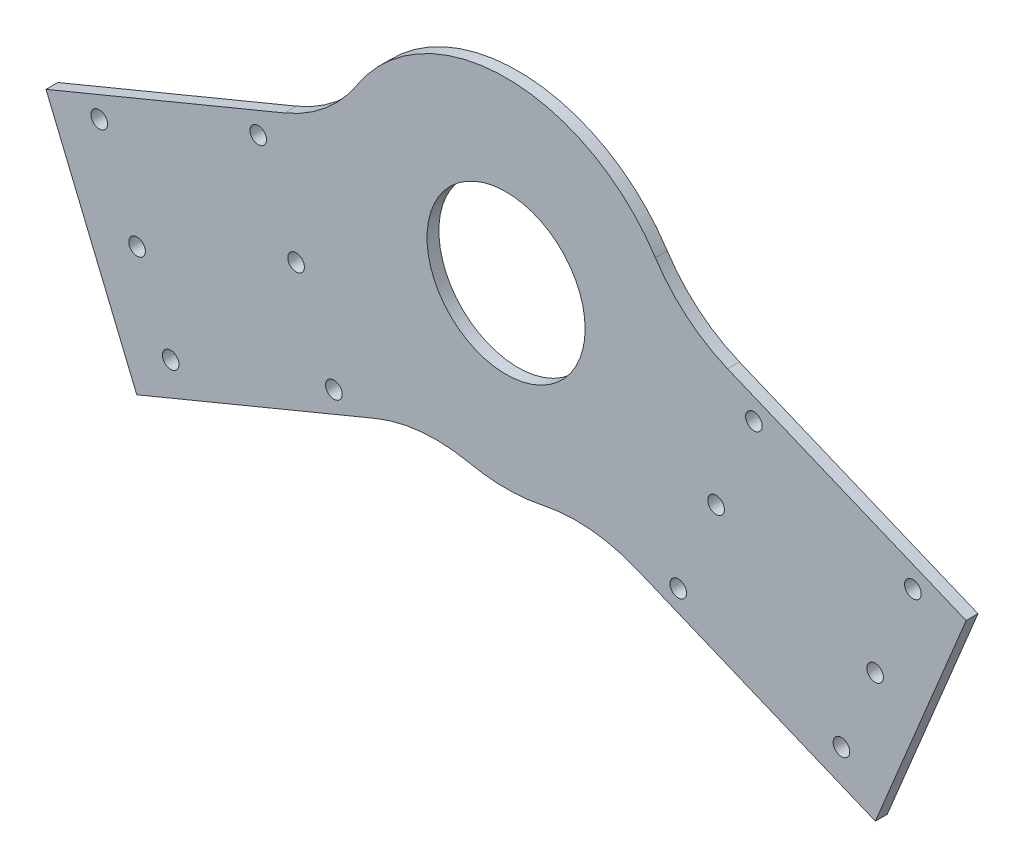
SolidWorks part; units mm, degrees
ref_plane "Front Plane" through (0, 0, 0) normal (0, 0, 1) x (1, 0, 0)
ref_plane "Top Plane" through (0, 0, 0) normal (0, 1, 0) x (1, 0, 0)
ref_plane "Right Plane" through (0, 0, 0) normal (1, 0, 0) x (0, 0, -1)
sketch "Sketch1" plane through (0, 0, 0) normal (0, 0, 1) x (1, 0, 0)
  line L0 (0, 0) -> (0, 50000) construction
  line L1 (0, 0) -> (50000, 0) construction
  line L2 (0, 0) -> (-935.0114, -387.2944) construction
  line L3 (0, 0) -> (18.1262, -8.4524) construction
  line L5 (-93.4177, -71.1667) -> (-116.3787, -15.7339)
  line L7 (-116.3787, -15.7339) -> (-42.4684, 14.8808)
  line L16 (0, 0) -> (935.0114, -387.2944) construction
  line L17 (116.3787, -15.7339) -> (42.4684, 14.8808)
  line L18 (-93.4177, -71.1667) -> (-19.5074, -40.552)
  line L19 (93.4177, -71.1667) -> (19.5074, -40.552)
  line L20 (93.4177, -71.1667) -> (116.3787, -15.7339)
  line L21 (-104.8302, -10.9503) -> (-81.8692, -66.3831) construction
  line L22 (-64.6045, 5.7117) -> (-41.6435, -49.7211) construction
  circle A2 centre (0, 0) radius 20
  arc A4 (42.4684, 14.8808) -> (-42.4684, 14.8808) centre (0, 0) ccw
  arc A6 (19.5074, -40.552) -> (-19.5074, -40.552) centre (0, 0) cw
  circle A7 centre (-93.3497, -38.6667) radius 2.1
  circle A8 centre (-102.9168, -15.5697) radius 2.1
  circle A9 centre (-84.8388, -59.214) radius 2.1
  circle A10 centre (84.8388, -59.214) radius 2.1
  circle A11 centre (93.3497, -38.6667) radius 2.1
  circle A12 centre (102.9168, -15.5697) radius 2.1
  circle A13 centre (-62.6911, 1.0923) radius 2.1
  circle A14 centre (-53.124, -22.0047) radius 2.1
  circle A15 centre (-43.5569, -45.1017) radius 2.1
  circle A16 centre (43.5569, -45.1017) radius 2.1
  circle A17 centre (53.124, -22.0047) radius 2.1
  circle A18 centre (62.6911, 1.0923) radius 2.1
  point P12 (-104.8982, -43.4503)
  dimension "D2" = 30
  dimension "D6" = 40
  dimension "D4" = 45
  dimension "D7" = 4.2
  dimension "D1" = 67.5
  dimension "D3" = 12.5
  dimension "D5" = 80
  dimension "D8" = 5
  dimension "D9" = 43.54
  dimension "D10" = 5
  dimension "D11" = 5
extrude "Boss-Extrude1" add sketch "Sketch1" along normal blind 3
fillet "Fillet1" radius 40 4 edges at (-42.4684, 14.8808, 1.5) (42.4684, 14.8808, 1.5) (19.5074, -40.552, 1.5) (-19.5074, -40.552, 1.5)
